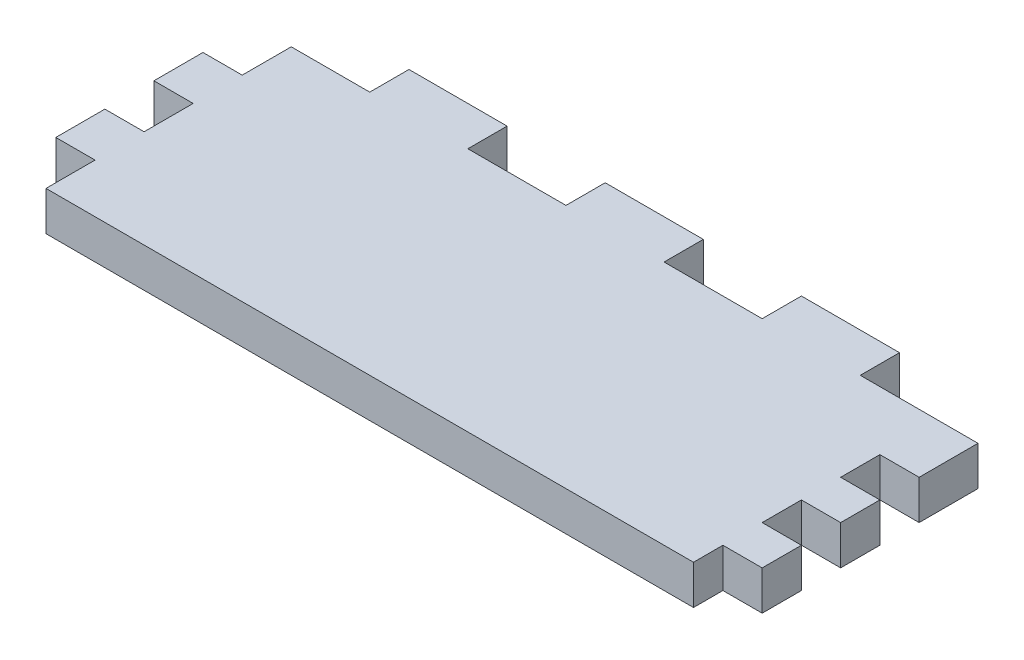
SolidWorks part; units mm, degrees
material "Maple"
ref_plane "Front Plane" through (0, 0, 0) normal (0, 0, 1) x (1, 0, 0)
ref_plane "Top Plane" through (0, 0, 0) normal (0, 1, 0) x (1, 0, 0)
ref_plane "Right Plane" through (0, 0, 0) normal (1, 0, 0) x (0, 0, -1)
sketch "Sketch1" plane through (0, 0, 0) normal (0, 1, 0) x (1, 0, 0)
  line L1 (0, 0) -> (66, 0)
  line L2 (0, 0) -> (0, -25)
  line L3 (0, -25) -> (66, -25)
  line L4 (66, 0) -> (66, -25)
  dimension "D1" = 66
  dimension "D2" = 25
extrude "Boss-Extrude1" add sketch "Sketch1" along normal blind 4
sketch "Sketch2" plane through (0, 4, 0) normal (0, 1, 0) x (1, 0, 0)
  line L0 (66, 0) -> (0, 0) construction
  line L10 (0, 0) -> (0, -25) construction
  line L11 (0, -5) -> (-4, -5)
  line L12 (0, -5) -> (0, -10)
  line L13 (0, -10) -> (-4, -10)
  line L14 (-4, -5) -> (-4, -10)
  point P4 (0, 0)
  point P9 (0, -4.8129)
  point P16 (0, 0)
  point P17 (0, 0)
  dimension "D1" = 4
  dimension "D2" = 5
  dimension "D3" = 5
extrude "Boss-Extrude2" add sketch "Sketch2" against normal through all
pattern_linear "LPattern1" count 2 spacing 10 along (0, 0, 1) of "Boss-Extrude2"
sketch "Sketch3" plane through (0, 4, 0) normal (0, 1, 0) x (1, 0, 0)
  line L0 (33, -25) -> (33, 0) construction
  line L1 (0, -25) -> (66, -25) construction
  line L2 (66, 0) -> (0, 0) construction
  line L4 (28, 0) -> (38, 0)
  line L5 (28, 0) -> (28, 4)
  line L6 (28, 4) -> (38, 4)
  line L7 (38, 0) -> (38, 4)
  line L8 (28, 0) -> (38, 4) construction
  line L9 (28, 4) -> (38, 0) construction
  point P6 (33, 2)
  dimension "D1" = 4
  dimension "D2" = 10
extrude "Boss-Extrude3" add sketch "Sketch3" against normal through all
pattern_linear "LPattern2" count 2 spacing 20 along (1, 0, 0) count 2 spacing 20 along (-1, 0, 0) of "Boss-Extrude3"
sketch "Sketch5" plane through (0, 4, 0) normal (0, 1, 0) x (1, 0, 0)
  line L0 (66, 0) -> (58, 0) construction
  line L1 (66, 0) -> (70, 0)
  line L2 (66, 0) -> (66, -6)
  line L3 (66, -6) -> (70, -6)
  line L4 (70, 0) -> (70, -6)
  line L5 (66, -25) -> (66, 0) construction
  line L7 (66, -10) -> (70, -10)
  line L8 (66, -10) -> (66, -14)
  line L9 (66, -14) -> (70, -14)
  line L10 (70, -10) -> (70, -14)
  line L11 (66, -18) -> (70, -18)
  line L12 (66, -18) -> (66, -22)
  line L13 (66, -22) -> (70, -22)
  line L14 (70, -18) -> (70, -22)
  dimension "D1" = 4
  dimension "D2" = 6
  dimension "D3" = 4
  dimension "D4" = 4
  dimension "D5" = 4
  dimension "D6" = 4
extrude "Boss-Extrude4" add sketch "Sketch5" against normal through all
